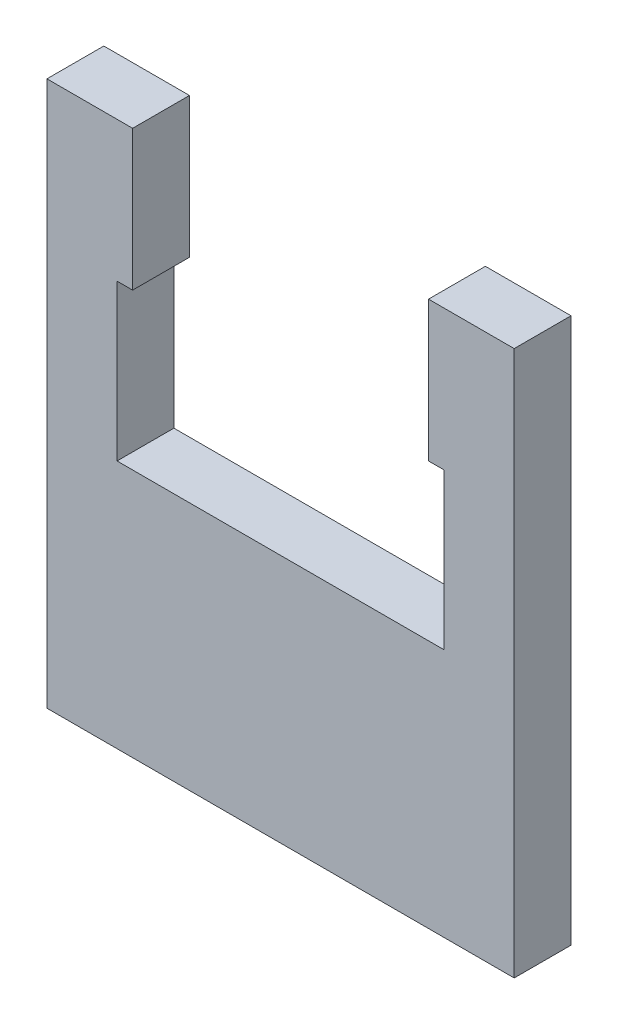
SolidWorks part; units mm, degrees
ref_plane "Front Plane" through (0, 0, 0) normal (1, 0, 0) x (0, 1, 0)
ref_plane "Top Plane" through (0, 0, 0) normal (0, 0, 1) x (0, 1, 0)
ref_plane "Right Plane" through (0, 0, 0) normal (0, 1, 0) x (-1, 0, 0)
sketch "Sketch1" plane through (0, 0, 0) normal (0, 0, 1) x (0, 1, 0)
  line L0 (0, 78.2005) -> (-22.86, 78.2005)
  line L1 (0, -16.5) -> (0, 16.5) construction
  line L2 (-22.86, 78.2005) -> (-22.86, 80.7405)
  line L3 (-22.86, 80.7405) -> (-48.26, 80.7405)
  line L4 (-48.26, 80.7405) -> (-48.26, 27.4005)
  line L5 (-48.26, 27.4005) -> (-22.86, 27.4005)
  line L6 (-22.86, 27.4005) -> (-22.86, 29.9405)
  line L7 (-22.86, 29.9405) -> (0, 29.9405)
  line L8 (0, 29.9405) -> (0, 15.9705)
  line L9 (0, 15.9705) -> (-88.9, 15.9705)
  line L10 (-88.9, 15.9705) -> (-88.9, 92.1705)
  line L11 (-88.9, 92.1705) -> (0, 92.1705)
  line L12 (0, 92.1705) -> (0, 78.2005)
  dimension "D1" = 48.26
  dimension "D2" = 53.34
  dimension "D3" = 76.2
  dimension "D4" = 40.64
  dimension "D5" = 25.4
  dimension "D6" = 22.86
extrude "Boss-Extrude1" add sketch "Sketch1" along normal blind 9.271
